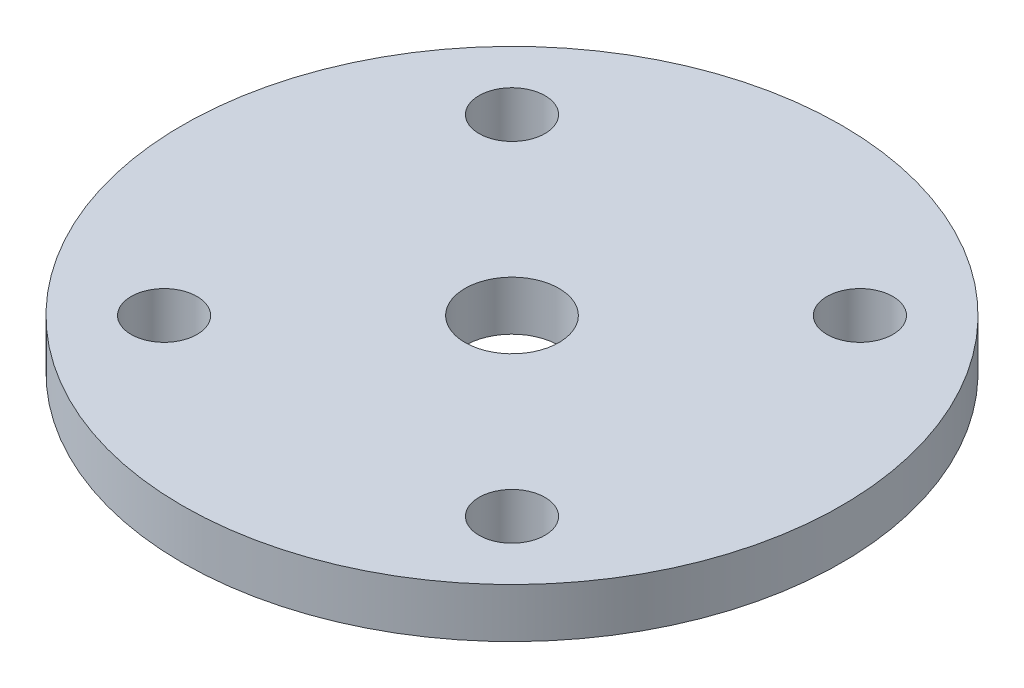
SolidWorks part; units mm, degrees
material "Policarbonato"
ref_plane "Plano frontal" through (0, 0, 0) normal (0, 0, 1) x (1, 0, 0)
ref_plane "Plano superior" through (0, 0, 0) normal (0, 1, 0) x (1, 0, 0)
ref_plane "Plano direito" through (0, 0, 0) normal (1, 0, 0) x (0, 0, -1)
ref_plane "Plano1" through (0, -3, 0) normal (0, -1, 0) x (1, 0, 0)
sketch "Esboço1" plane through (0, -3, 0) normal (0, -1, 0) x (1, 0, 0)
  circle A0 centre (0, 0) radius 2.85
  circle A1 centre (10.5571, 10.5571) radius 2
  circle A2 centre (10.5571, -10.5571) radius 2
  circle A3 centre (-10.5571, -10.5571) radius 2
  circle A4 centre (-10.5571, 10.5571) radius 2
  circle A5 centre (0, 0) radius 20
  point P14 (0, 0)
  dimension "D1" = 4
  dimension "D2" = 40
  dimension "D3" = 5.7
  dimension "D4" = 14.93
  dimension "D5" = 4
extrude "Ressalto-extrusão1" add sketch "Esboço1" against normal blind 3
